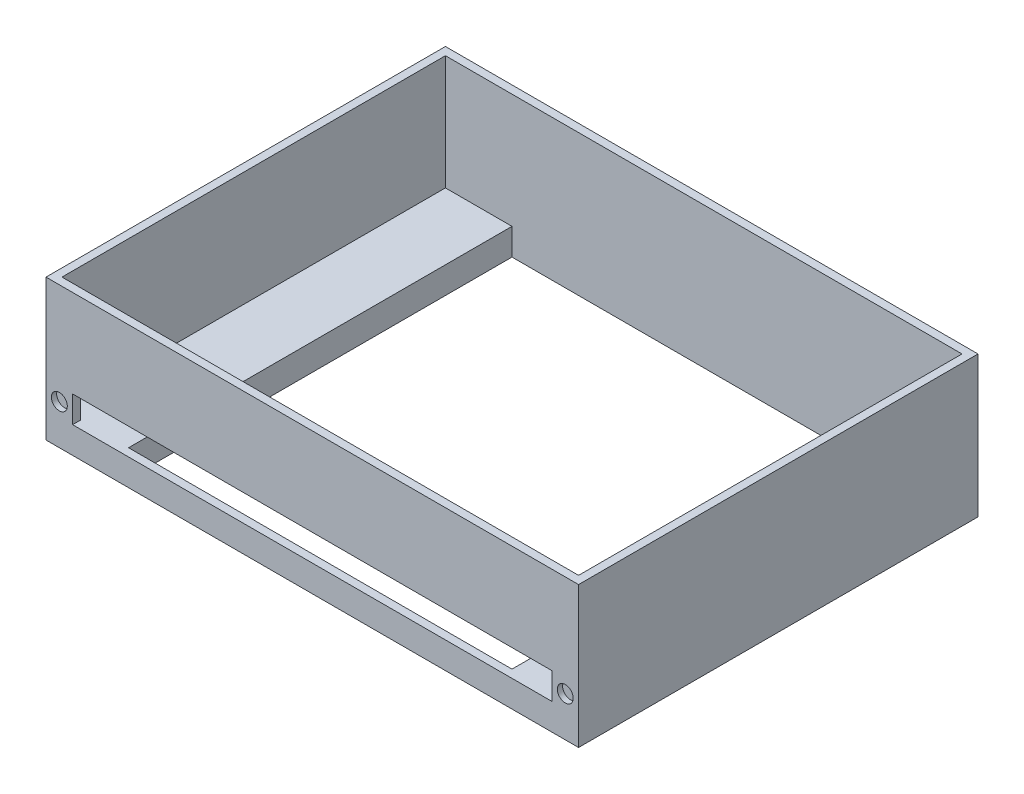
SolidWorks part; units mm, degrees
ref_plane "Front Plane" through (0, 0, 0) normal (0, 0, 1) x (1, 0, 0)
ref_plane "Top Plane" through (0, 0, 0) normal (0, 1, 0) x (1, 0, 0)
ref_plane "Right Plane" through (0, 0, 0) normal (1, 0, 0) x (0, 0, -1)
sketch "Sketch2" plane through (0, 0, 0) normal (0, 1, 0) x (1, 0, 0)
  line L1 (-100, 75) -> (100, 75)
  line L2 (-100, 75) -> (-100, -75)
  line L3 (-100, -75) -> (100, -75)
  line L4 (100, 75) -> (100, -75)
  line L5 (-100, 75) -> (100, -75) construction
  line L6 (-100, -75) -> (100, 75) construction
  point P0 (0, 0)
  dimension "D1" = 200
  dimension "D2" = 150
extrude "Boss-Extrude1" add sketch "Sketch2" along normal blind 3
sketch "Sketch3" plane through (0, 3, 0) normal (0, 1, 0) x (1, 0, 0)
  line L8 (100, -75) -> (100, 75)
  line L9 (100, 75) -> (-100, 75)
  line L10 (-100, 75) -> (-100, -75)
  line L11 (-100, -75) -> (100, -75)
  line L12 (100, -75) -> (100, 75)
  line L13 (100, 75) -> (-100, 75)
  line L14 (-100, 75) -> (-100, -75)
  line L15 (-100, -75) -> (100, -75)
  line L20 (97, -72) -> (97, 72)
  line L21 (97, 72) -> (-97, 72)
  line L22 (-97, 72) -> (-97, -72)
  line L23 (-97, -72) -> (97, -72)
  line L24 (97, -72) -> (97, 72)
  line L25 (97, 72) -> (-97, 72)
  line L26 (-97, 72) -> (-97, -72)
  line L27 (-97, -72) -> (97, -72)
  dimension "D1" = 0
  dimension "D2" = 3
extrude "Boss-Extrude2" add sketch "Sketch3" along normal blind 50
sketch "Sketch4" plane through (0, 0, 75) normal (0, 0, 1) x (1, 0, 0)
  line L0 (0, 53) -> (0, 0) construction
  line L1 (-100, 53) -> (100, 53) construction
  line L2 (-100, 0) -> (100, 0) construction
  line L4 (-90, 20) -> (90, 20)
  line L5 (-90, 20) -> (-90, 10)
  line L6 (-90, 10) -> (90, 10)
  line L7 (90, 20) -> (90, 10)
  line L8 (-90, 20) -> (90, 10) construction
  line L9 (-90, 10) -> (90, 20) construction
  point P6 (0, 15)
  dimension "D1" = 180
  dimension "D2" = 10
  dimension "D3" = 15
extrude "Cut-Extrude3" cut sketch "Sketch4" against normal up to surface (147 mm away) up to face at (0, 28, -72)
sketch "Sketch5" plane through (97, 0, 0) normal (-1, 0, 0) x (0, 0, 1)
  line L0 (0, 53) -> (0, 3) construction
  line L1 (72, 53) -> (-72, 53) construction
  line L2 (72, 3) -> (-72, 3) construction
  line L3 (-72, 53) -> (-72, 3) construction
  line L4 (72, 10) -> (-72, 10)
  line L5 (72, 10) -> (72, 3)
  line L6 (72, 3) -> (-72, 3)
  line L7 (-72, 10) -> (-72, 3)
  line L8 (72, 10) -> (-72, 3) construction
  line L9 (72, 3) -> (-72, 10) construction
  point P6 (0, 6.5)
  dimension "D1" = 7
  dimension "D2" = 3.5
extrude "Boss-Extrude3" add sketch "Sketch5" along normal blind 25
sketch "Sketch6" plane through (-97, 0, 0) normal (1, 0, 0) x (0, 0, -1)
  line L0 (0, 53) -> (0, 3) construction
  line L1 (72, 53) -> (-72, 53) construction
  line L2 (72, 3) -> (-72, 3) construction
  line L3 (72, 53) -> (72, 3) construction
  line L4 (-72, 3) -> (72, 3)
  line L5 (-72, 3) -> (-72, 10)
  line L6 (-72, 10) -> (72, 10)
  line L7 (72, 3) -> (72, 10)
  line L8 (-72, 3) -> (72, 10) construction
  line L9 (-72, 10) -> (72, 3) construction
  point P6 (0, 6.5)
  dimension "D1" = 7
  dimension "D2" = 3.5
extrude "Boss-Extrude4" add sketch "Sketch6" along normal blind 25
sketch "Sketch7" plane through (0, 3, 0) normal (0, 1, 0) x (1, 0, 0)
  line L8 (72, 72) -> (-72, 72)
  line L9 (-72, 72) -> (-72, -72)
  line L10 (-72, -72) -> (72, -72)
  line L11 (72, -72) -> (72, 72)
  line L12 (72, 72) -> (-72, 72)
  line L13 (-72, 72) -> (-72, -72)
  line L14 (-72, -72) -> (72, -72)
  line L15 (72, -72) -> (72, 72)
  dimension "D1" = 0
extrude "Cut-Extrude5" cut sketch "Sketch7" against normal through all
sketch "Sketch8" plane through (0, 0, 75) normal (0, 0, 1) x (1, 0, 0)
  line L0 (0, 20) -> (0, 10) construction
  line L1 (90, 20) -> (-90, 20) construction
  line L2 (-90, 10) -> (90, 10) construction
  line L3 (-90, 15) -> (100, 15) construction
  line L4 (-90, 20) -> (-90, 10) construction
  line L5 (100, 53) -> (100, 0) construction
  line L6 (-90, 15) -> (-100, 15) construction
  line L7 (-100, 53) -> (-100, 0) construction
  line L8 (90, 10) -> (90, 20) construction
  circle A0 centre (-95, 15) radius 3
  circle A1 centre (95, 15) radius 3
  dimension "D2" = 6
  dimension "D3" = 6
  dimension "D1" = 5
extrude "Cut-Extrude6" cut sketch "Sketch8" against normal blind 2
sketch "Sketch9" plane through (0, 0, 0) normal (0, -1, 0) x (1, 0, 0)
  line L0 (-100, 0) -> (100, 0) construction
  line L1 (-100, -75) -> (-100, 75) construction
  line L2 (100, 75) -> (100, -75) construction
  line L3 (-100, 75) -> (100, 75) construction
  line L4 (100, -75) -> (-100, -75) construction
  circle A0 centre (-95, 70) radius 1.5
  circle A1 centre (95, 70) radius 1.5
  circle A2 centre (95, -70) radius 1.5
  circle A3 centre (-95, -70) radius 1.5
  point P16 (0, 0)
  point P18 (-100, 65.4882)
  point P20 (0, 0)
  dimension "D3" = 3
  dimension "D6" = 3
  dimension "D9" = 3
  dimension "D12" = 3
  dimension "D1" = 5
  dimension "D2" = 5
  dimension "D4" = 5
  dimension "D5" = 5
  dimension "D7" = 5
  dimension "D8" = 5
  dimension "D10" = 5
  dimension "D11" = 5
extrude "Cut-Extrude7" cut sketch "Sketch9" against normal blind 8
equation "\"len\"= 200"
equation "\"D1@Sketch2\"=\"len\""
equation "\"width\"=150"
equation "\"D2@Sketch2\"=\"width\""
equation "\"thickness_01\"=3"
equation "\"D1@Boss-Extrude1\"=\"thickness_01\""
equation "\"hight\"=50"
equation "\"D1@Boss-Extrude2\"=\"hight\""
equation "\"hole_len\"=180"
equation "\"D1@Sketch4\"=\"hole_len\""
equation "\"hole_width\"=10"
equation "\"D2@Sketch4\"=\"hole_width\""
equation "\"gap\"=15"
equation "\"D3@Sketch4\"=\"gap\""
equation "\"botom_dis\"= 7"
equation "\"D1@Sketch5\"=\"botom_dis\""
equation "\"D2@Sketch5\"=\"botom_dis\"/2"
equation "\"support\"=25"
equation "\"D1@Boss-Extrude3\"=\"support\""
equation "\"D1@Sketch6\"=\"botom_dis\""
equation "\"D2@Sketch6\"=\"botom_dis\"/2"
equation "\"D1@Boss-Extrude4\"=\"support\""
